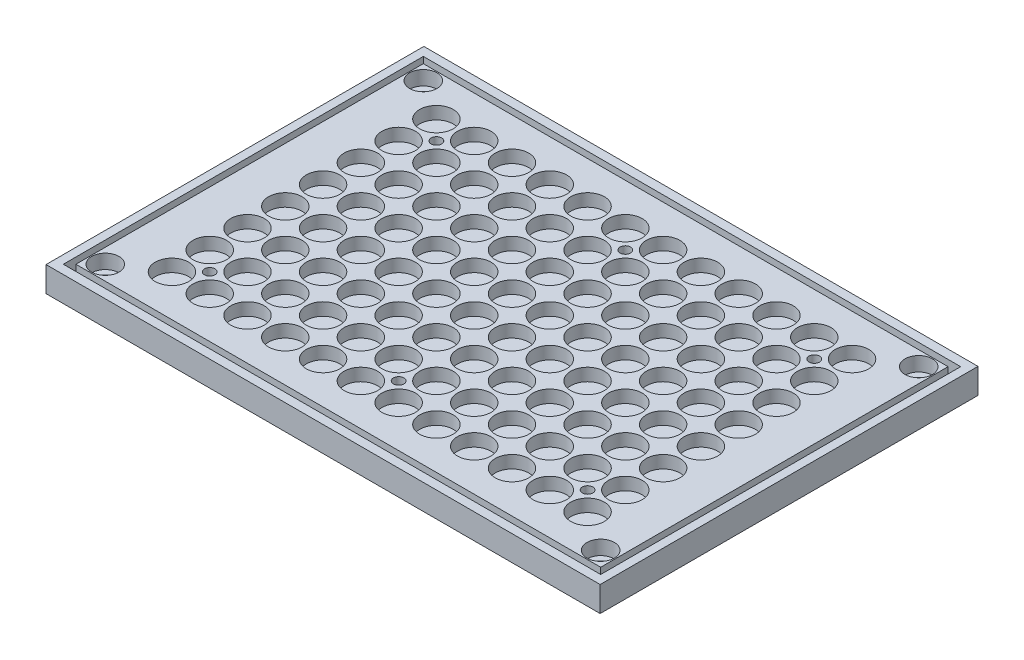
SolidWorks part; units mm, degrees
ref_plane "Front Plane" through (0, 0, 0) normal (0, 0, 1) x (1, 0, 0)
ref_plane "Top Plane" through (0, 0, 0) normal (0, 1, 0) x (1, 0, 0)
ref_plane "Right Plane" through (0, 0, 0) normal (1, 0, 0) x (0, 0, -1)
sketch "Sketch1" plane through (0, 0, 0) normal (0, 1, 0) x (1, 0, 0)
  line L1 (-66, -45) -> (66, -45)
  line L2 (-66, -45) -> (-66, 45)
  line L3 (-66, 45) -> (66, 45)
  line L4 (66, -45) -> (66, 45)
  line L5 (-66, -45) -> (66, 45) construction
  line L6 (-66, 45) -> (66, -45) construction
  point P0 (0, 0)
  dimension "D1" = 90
  dimension "D2" = 132
extrude "Boss-Extrude1" add sketch "Sketch1" along normal blind 6
sketch "Sketch2" plane through (0, 6, 0) normal (0, 1, 0) x (1, 0, 0)
  line L0 (-62.5, 41.375) -> (62.5, 41.375)
  line L1 (-64, -42.875) -> (64, -42.875)
  line L2 (-64, -42.875) -> (-64, 42.875)
  line L3 (-64, 42.875) -> (64, 42.875)
  line L4 (64, -42.875) -> (64, 42.875)
  line L5 (-64, -42.875) -> (64, 42.875) construction
  line L6 (-64, 42.875) -> (64, -42.875) construction
  line L7 (62.5, -41.375) -> (62.5, 41.375)
  line L8 (-62.5, -41.375) -> (62.5, -41.375)
  line L9 (-62.5, -41.375) -> (-62.5, 41.375)
  point P0 (0, 0)
  dimension "D1" = 128
  dimension "D2" = 85.75
  dimension "D3" = 1.5
extrude "Cut-Extrude1" cut sketch "Sketch2" against normal blind 3
sketch "Sketch3" plane through (0, 6, 0) normal (0, 1, 0) x (1, 0, 0)
  line L1 (-4.5, -4.5) -> (4.5, -4.5) construction
  line L2 (-4.5, -4.5) -> (-4.5, 4.5) construction
  line L3 (-4.5, 4.5) -> (4.5, 4.5) construction
  line L4 (4.5, -4.5) -> (4.5, 4.5) construction
  line L5 (-4.5, -4.5) -> (4.5, 4.5) construction
  line L6 (-4.5, 4.5) -> (4.5, -4.5) construction
  circle A0 centre (-49.5, 31.5) radius 4
  circle A1 centre (-40.5, 31.5) radius 4
  circle A2 centre (-31.5, 31.5) radius 4
  circle A3 centre (-22.5, 31.5) radius 4
  circle A4 centre (-13.5, 31.5) radius 4
  circle A5 centre (-4.5, 31.5) radius 4
  circle A6 centre (4.5, 31.5) radius 4
  circle A7 centre (13.5, 31.5) radius 4
  circle A8 centre (22.5, 31.5) radius 4
  circle A9 centre (31.5, 31.5) radius 4
  circle A10 centre (40.5, 31.5) radius 4
  circle A11 centre (49.5, 31.5) radius 4
  circle A12 centre (-40.5, 22.5) radius 4
  circle A13 centre (-31.5, 22.5) radius 4
  circle A14 centre (-22.5, 22.5) radius 4
  circle A15 centre (-13.5, 22.5) radius 4
  circle A16 centre (-4.5, 22.5) radius 4
  circle A17 centre (4.5, 22.5) radius 4
  circle A18 centre (13.5, 22.5) radius 4
  circle A19 centre (22.5, 22.5) radius 4
  circle A20 centre (31.5, 22.5) radius 4
  circle A21 centre (40.5, 22.5) radius 4
  circle A22 centre (49.5, 22.5) radius 4
  circle A23 centre (-40.5, 13.5) radius 4
  circle A24 centre (-31.5, 13.5) radius 4
  circle A25 centre (-22.5, 13.5) radius 4
  circle A26 centre (-13.5, 13.5) radius 4
  circle A27 centre (-4.5, 13.5) radius 4
  circle A28 centre (4.5, 13.5) radius 4
  circle A29 centre (13.5, 13.5) radius 4
  circle A30 centre (22.5, 13.5) radius 4
  circle A31 centre (31.5, 13.5) radius 4
  circle A32 centre (40.5, 13.5) radius 4
  circle A33 centre (49.5, 13.5) radius 4
  circle A34 centre (-40.5, 4.5) radius 4
  circle A35 centre (-31.5, 4.5) radius 4
  circle A36 centre (-22.5, 4.5) radius 4
  circle A37 centre (-13.5, 4.5) radius 4
  circle A38 centre (-4.5, 4.5) radius 4
  circle A39 centre (4.5, 4.5) radius 4
  circle A40 centre (13.5, 4.5) radius 4
  circle A41 centre (22.5, 4.5) radius 4
  circle A42 centre (31.5, 4.5) radius 4
  circle A43 centre (40.5, 4.5) radius 4
  circle A44 centre (49.5, 4.5) radius 4
  circle A45 centre (-40.5, -4.5) radius 4
  circle A46 centre (-31.5, -4.5) radius 4
  circle A47 centre (-22.5, -4.5) radius 4
  circle A48 centre (-13.5, -4.5) radius 4
  circle A49 centre (-4.5, -4.5) radius 4
  circle A50 centre (4.5, -4.5) radius 4
  circle A51 centre (13.5, -4.5) radius 4
  circle A52 centre (22.5, -4.5) radius 4
  circle A53 centre (31.5, -4.5) radius 4
  circle A54 centre (40.5, -4.5) radius 4
  circle A55 centre (49.5, -4.5) radius 4
  circle A56 centre (-40.5, -13.5) radius 4
  circle A57 centre (-31.5, -13.5) radius 4
  circle A58 centre (-22.5, -13.5) radius 4
  circle A59 centre (-13.5, -13.5) radius 4
  circle A60 centre (-4.5, -13.5) radius 4
  circle A61 centre (4.5, -13.5) radius 4
  circle A62 centre (13.5, -13.5) radius 4
  circle A63 centre (22.5, -13.5) radius 4
  circle A64 centre (31.5, -13.5) radius 4
  circle A65 centre (40.5, -13.5) radius 4
  circle A66 centre (49.5, -13.5) radius 4
  circle A67 centre (-40.5, -22.5) radius 4
  circle A68 centre (-31.5, -22.5) radius 4
  circle A69 centre (-22.5, -22.5) radius 4
  circle A70 centre (-13.5, -22.5) radius 4
  circle A71 centre (-4.5, -22.5) radius 4
  circle A72 centre (4.5, -22.5) radius 4
  circle A73 centre (13.5, -22.5) radius 4
  circle A74 centre (22.5, -22.5) radius 4
  circle A75 centre (31.5, -22.5) radius 4
  circle A76 centre (40.5, -22.5) radius 4
  circle A77 centre (49.5, -22.5) radius 4
  circle A78 centre (-40.5, -31.5) radius 4
  circle A79 centre (-31.5, -31.5) radius 4
  circle A80 centre (-22.5, -31.5) radius 4
  circle A81 centre (-13.5, -31.5) radius 4
  circle A82 centre (-4.5, -31.5) radius 4
  circle A83 centre (4.5, -31.5) radius 4
  circle A84 centre (13.5, -31.5) radius 4
  circle A85 centre (22.5, -31.5) radius 4
  circle A86 centre (31.5, -31.5) radius 4
  circle A87 centre (40.5, -31.5) radius 4
  circle A88 centre (49.5, -31.5) radius 4
  circle A89 centre (-49.5, 22.5) radius 4
  circle A90 centre (-49.5, 13.5) radius 4
  circle A91 centre (-49.5, 4.5) radius 4
  circle A92 centre (-49.5, -4.5) radius 4
  circle A93 centre (-49.5, -13.5) radius 4
  circle A94 centre (-49.5, -22.5) radius 4
  circle A95 centre (-49.5, -31.5) radius 4
  point P2 (0, 0)
  point P3 (-3.1163, 3.5661)
  point P194 (0, 0)
  point P195 (-3.5516, -6.3841)
  dimension "D1" = 8
  dimension "D4" = 9
  dimension "D5" = 9
  dimension "D2" = 12
  dimension "D3" = 8
extrude "Cut-Extrude2" cut sketch "Sketch3" against normal blind 3
sketch "Sketch4" plane through (0, 6, 0) normal (0, 1, 0) x (1, 0, 0)
  line L1 (-45, -27) -> (45, -27) construction
  line L2 (-45, -27) -> (-45, 27) construction
  line L3 (-45, 27) -> (45, 27) construction
  line L4 (45, -27) -> (45, 27) construction
  line L5 (-45, -27) -> (45, 27) construction
  line L6 (-45, 27) -> (45, -27) construction
  line L8 (-49.5, 22.5) -> (-40.5, 22.5) construction
  line L9 (-49.5, 22.5) -> (-49.5, 31.5) construction
  line L10 (-49.5, 31.5) -> (-40.5, 31.5) construction
  line L11 (-40.5, 22.5) -> (-40.5, 31.5) construction
  line L12 (-49.5, 22.5) -> (-40.5, 31.5) construction
  line L13 (-49.5, 31.5) -> (-40.5, 22.5) construction
  circle A1 centre (-40.5, 22.5) radius 4 construction
  circle A2 centre (-40.5, 22.5) radius 4 construction
  point P0 (0, 0)
  point P6 (0, 27)
  point P7 (0, -27)
  point P14 (0, 0)
  point P16 (0, 0)
  dimension "D2" = 90
  dimension "D3" = 54
hole_wizard "Tap Drill for M3 Tap1" positions "3DSketch1" profile "Sketch5" hole size "M3" standard "ISO" end condition through all
sketch3d "3DSketch1"
  point P0 (-45, 6, -27)
  point P3 (0, 6, -27)
  point P6 (45, 6, -27)
  point P9 (45, 6, 27)
  point P12 (0, 6, 27)
  point P15 (-45, 6, 27)
sketch "Sketch5" plane through (-45, 6, -27) normal (1, 0, 0) x (0, 0, 1)
  line L0 (0, 0) -> (0, 6)
  line L1 (0, 6) -> (1.25, 6)
  line L2 (1.25, 6) -> (1.25, 0)
  line L5 (1.25, 0) -> (0, 0)
  line L11 (0, -6.35) -> (0, 107.95) construction
  dimension "Thru Hole Dia." = 2.5
  dimension "Thru Hole Depth" = 6
sketch "Sketch6" plane through (0, 6, 0) normal (0, 1, 0) x (1, 0, 0)
  line L0 (-45, -27) -> (45, 27) construction
  line L1 (-59, -37.875) -> (59, -37.875) construction
  line L2 (-59, -37.875) -> (-59, 37.875) construction
  line L3 (-59, 37.875) -> (59, 37.875) construction
  line L4 (59, -37.875) -> (59, 37.875) construction
  line L5 (-59, -37.875) -> (59, 37.875) construction
  line L6 (-59, 37.875) -> (59, -37.875) construction
  line L7 (-62.5, 41.375) -> (-62.5, -41.375) construction
  line L9 (62.5, 41.375) -> (-62.5, 41.375) construction
  point P0 (0, 0)
  dimension "D1" = 3.5
  dimension "D2" = 3.5
hole_wizard "CBORE for M3 Hex Socket Head Cap Screw2" positions "3DSketch2" profile "Sketch7" counterbore size "M3" standard "ISO" end condition through all
sketch3d "3DSketch2"
  point P0 (-59, 6, -37.875)
  point P3 (59, 6, -37.875)
  point P6 (-59, 6, 37.875)
  point P9 (59, 6, 37.875)
sketch "Sketch7" plane through (-59, 6, -37.875) normal (1, 0, 0) x (0, 0, 1)
  line L0 (0, 0) -> (0, 6)
  line L1 (0, 6) -> (1.7, 6)
  line L3 (1.7, 6) -> (1.7, 3.4)
  line L4 (1.7, 3.4) -> (3.25, 3.4)
  line L5 (3.25, 3.4) -> (3.25, 0)
  line L7 (3.25, 0) -> (0, 0)
  line L11 (0, -6.35) -> (0, 107.95) construction
  dimension "Thru Hole Dia." = 3.4
  dimension "Thru Hole Depth" = 6
  dimension "C'Bore Dia." = 6.5
  dimension "C'Bore Depth" = 3.4
